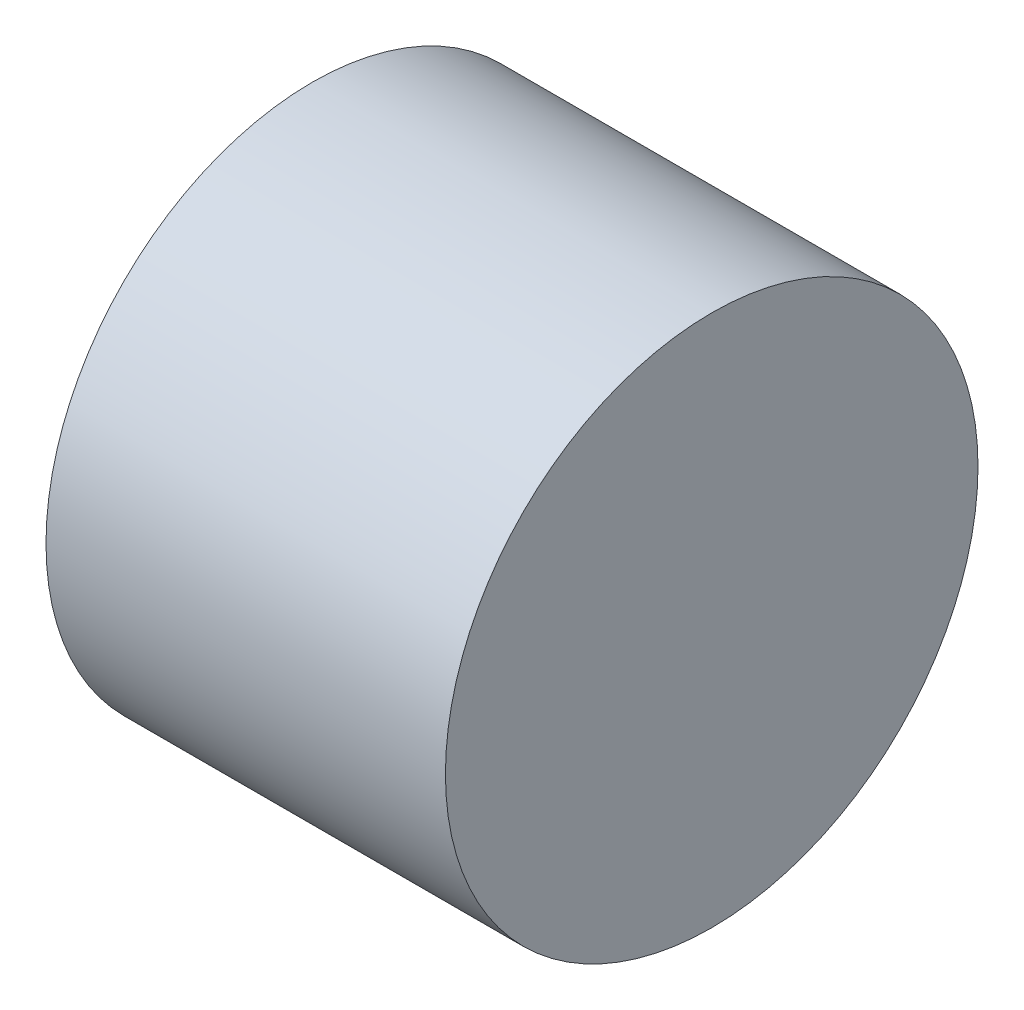
SolidWorks part; units mm, degrees
material "Cast Alloy Steel"
ref_plane "Front Plane" through (0, 0, 0) normal (0, 0, 1) x (1, 0, 0)
ref_plane "Top Plane" through (0, 0, 0) normal (0, 1, 0) x (1, 0, 0)
ref_plane "Right Plane" through (0, 0, 0) normal (1, 0, 0) x (0, 0, -1)
sketch "Sketch1" plane through (0, 0, 0) normal (1, 0, 0) x (0, 0, -1)
  circle A0 centre (0, 0) radius 20
  dimension "D1" = 40
extrude "Extrude1" add sketch "Sketch1" along normal blind 30
